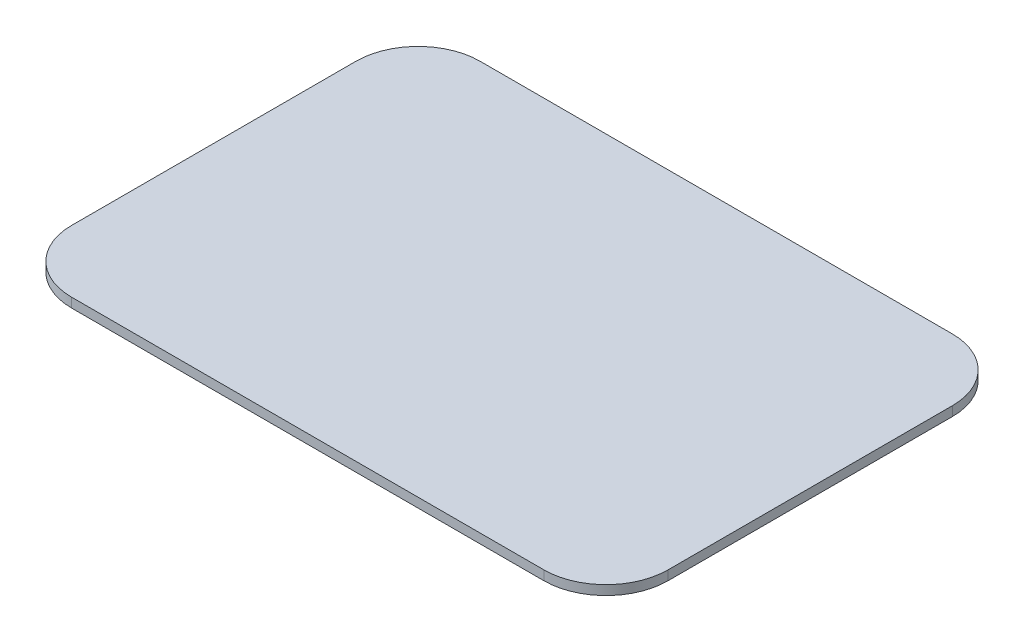
SolidWorks part; units mm, degrees
ref_plane "前视基准面" through (0, 0, 0) normal (0, 0, 1) x (1, 0, 0)
ref_plane "上视基准面" through (0, 0, 0) normal (0, 1, 0) x (1, 0, 0)
ref_plane "右视基准面" through (0, 0, 0) normal (1, 0, 0) x (0, 0, -1)
sketch "草图1" plane through (0, 0, 0) normal (0, 1, 0) x (1, 0, 0)
  line L0 (-50, 43.2523) -> (50, 43.2523)
  line L1 (-63.15, 30.1023) -> (-63.15, -30.1023)
  line L7 (63.15, 30.1023) -> (63.15, -30.1023)
  line L9 (-50, -43.2523) -> (50, -43.2523)
  arc A0 (-50, 43.2523) -> (-63.15, 30.1023) centre (-50, 30.1023) ccw
  arc A1 (50, 43.2523) -> (63.15, 30.1023) centre (50, 30.1023) cw
  arc A2 (50, -43.2523) -> (63.15, -30.1023) centre (50, -30.1023) ccw
  arc A3 (-50, -43.2523) -> (-63.15, -30.1023) centre (-50, -30.1023) cw
  point P12 (0, 43.2523)
  point P14 (63.15, 0)
  point P19 (-63.15, 0)
extrude "凸台-拉伸1" add sketch "草图1" along normal blind 2
